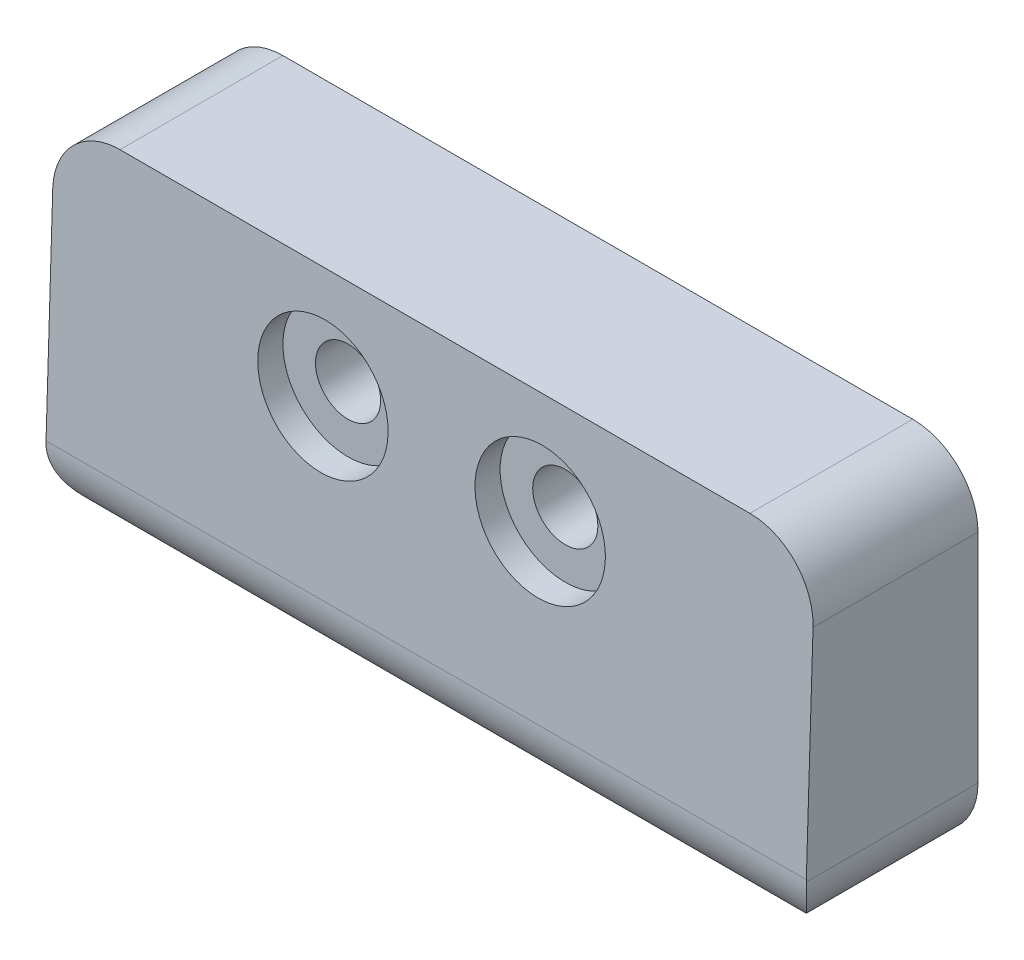
SolidWorks part; units mm, degrees
ref_plane "前视基准面" through (0, 0, 0) normal (0, 0, 1) x (1, 0, 0)
ref_plane "上视基准面" through (0, 0, 0) normal (0, 1, 0) x (1, 0, 0)
ref_plane "右视基准面" through (0, 0, 0) normal (1, 0, 0) x (0, 0, -1)
other "Configuration Table"
sketch "草图1" plane through (0, 0, 0) normal (0, 0, 1) x (1, 0, 0)
  line L1 (0, -55) -> (0, 55) construction
  line L3 (-17.5, 5) -> (17.5, 5)
  line L4 (-17.5, 5) -> (-17.5, -5)
  line L5 (-17.5, -5) -> (17.5, -5)
  line L6 (17.5, 5) -> (17.5, -5)
  line L7 (-17.5, 5) -> (17.5, -5) construction
  line L8 (-17.5, -5) -> (17.5, 5) construction
  circle A0 centre (-5, 0) radius 1.5
  circle A1 centre (5, 0) radius 1.5
  point P3 (0, 0)
  dimension "D1" = 3
  dimension "D2" = 5
  dimension "D3" = 35
  dimension "D4" = 10
extrude "凸台-拉伸1" add sketch "草图1" along normal blind 8
sketch "草图2" plane through (0, 0, 8) normal (0, 0, 1) x (1, 0, 0)
  circle A0 centre (-5, 0) radius 1.5 construction
  circle A1 centre (5, 0) radius 1.5 construction
  circle A2 centre (-5, 0) radius 1.5
  circle A3 centre (5, 0) radius 1.5
  circle A4 centre (-5, 0) radius 3
  circle A5 centre (5, 0) radius 3
  dimension "D1" = 1.5
extrude "切除-拉伸1" cut sketch "草图2" against normal blind 1.5
sketch "草图3" plane through (0, 0, 8) normal (0, 0, 1) x (1, 0, 0)
  line L0 (-17.5, -5) -> (17.5, -5) construction
  line L1 (-17.5, -5) -> (17.5, -5)
  line L3 (-17.5, -5) -> (17.5, -5)
  line L4 (-17.5, -5) -> (-17.5, -11)
  line L5 (-17.5, -11) -> (17.5, -11)
  line L6 (17.5, -5) -> (17.5, -11)
  line M7 (-17.5, -5) -> (17.5, -5)
  dimension "D1" = 6
extrude "凸台-拉伸2" add sketch "草图3" against normal up to surface (8 mm away) contours L6 L4 L5 M7 up to face at (0, 0, 0)
sketch "草图4" plane through (-17.5, 0, 0) normal (-1, 0, 0) x (0, 0, 1)
  line L0 (7.5, 5) -> (8, -11)
  line L4 (0, 5) -> (0, -11)
  line L5 (0, -11) -> (8, -11)
  line L6 (8, -11) -> (8, 5)
  line L7 (8, 5) -> (0, 5)
  line L8 (0, 5) -> (0, -11)
  line L9 (0, -11) -> (8, -11)
  line L10 (8, -11) -> (8, 5)
  line L11 (8, 5) -> (0, 5)
  line M7 (8, -11) -> (8, 5)
  line M8 (8, 5) -> (0, 5)
  dimension "D2" = 0.5
  dimension "D1" = 0
extrude "切除-拉伸2" cut sketch "草图4" against normal through all contours L0 M8 M7
fillet "圆角2" radius 3 5 edges at (0, -11, 8) (17.5, 5, 3.75) (17.5, -11, 4) (-17.5, -11, 4) (-17.5, 5, 3.75)
